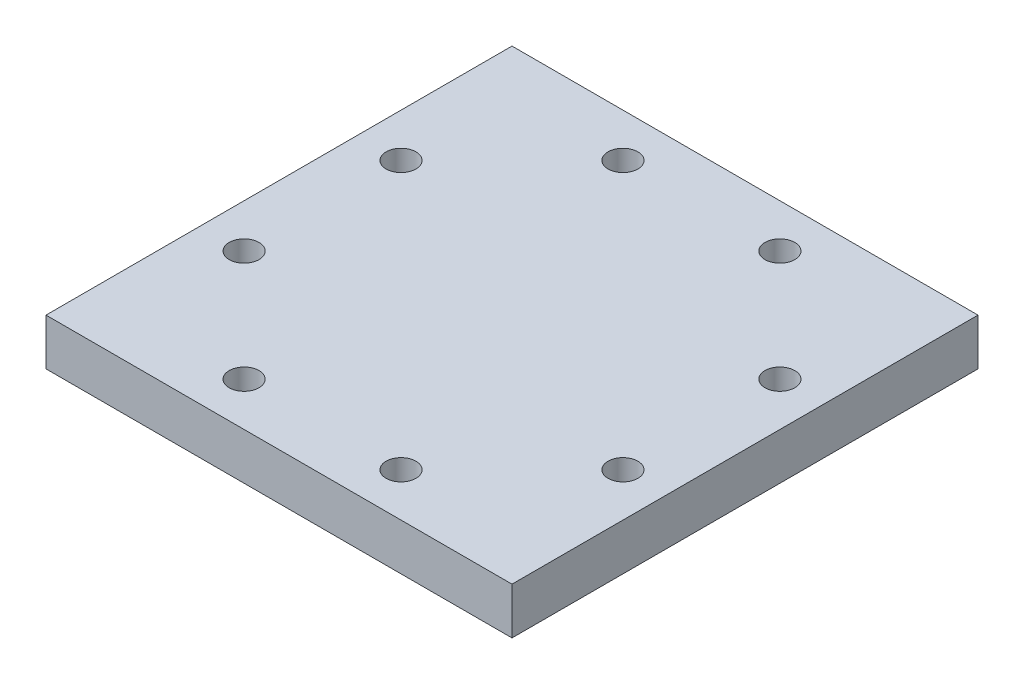
SolidWorks part; units mm, degrees
material "Alliage 1060"
ref_plane "Front" through (0, 0, 0) normal (0, 0, 1) x (1, 0, 0)
ref_plane "Top" through (0, 0, 0) normal (0, 1, 0) x (1, 0, 0)
ref_plane "Right" through (0, 0, 0) normal (1, 0, 0) x (0, 0, -1)
sketch "Esquisse1" plane through (0, 0, 0) normal (0, 1, 0) x (1, 0, 0)
  line L1 (-25, 25) -> (25, 25)
  line L2 (-25, 25) -> (-25, -25)
  line L3 (-25, -25) -> (25, -25)
  line L4 (25, 25) -> (25, -25)
  line L5 (-25, 25) -> (25, -25) construction
  line L6 (-25, -25) -> (25, 25) construction
  point P0 (0, 0)
  dimension "D1" = 50
  dimension "D2" = 50
extrude "Boss.-Extru.1" add sketch "Esquisse1" along normal blind 5
hole_wizard "Dégagement M31" positions "Esquisse4" profile "Esquisse5" hole size "M3" standard "ISO" end condition through all
sketch "Esquisse4" plane through (0, 5, 0) normal (0, 1, 0) x (1, 0, 0)
  point P0 (20.3253, 8.419)
  point P3 (8.419, 20.3253)
  point P6 (-8.419, 20.3253)
  point P9 (-20.3253, 8.419)
  point P12 (-20.3253, -8.419)
  point P15 (-8.419, -20.3253)
  point P18 (8.419, -20.3253)
  point P21 (20.3253, -8.419)
sketch "Esquisse5" plane through (20.3253, 5, -8.419) normal (1, 0, 0) x (0, 0, 1)
  line L0 (0, 0) -> (0, 5)
  line L1 (0, 5) -> (1.6, 5)
  line L2 (1.6, 5) -> (1.6, 0)
  line L5 (1.6, 0) -> (0, 0)
  line L11 (0, -6.35) -> (0, 107.95) construction
  dimension "Diamètre du perçage jusqu'au prochain" = 3.2
  dimension "Profondeur du perçage jusqu'au prochain" = 5
